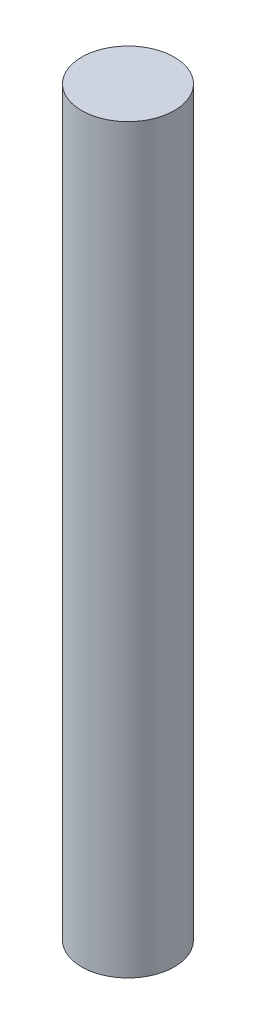
SolidWorks part; units mm, degrees
ref_plane "前视基准面" through (0, 0, 0) normal (0, 0, 1) x (1, 0, 0)
ref_plane "上视基准面" through (0, 0, 0) normal (0, 1, 0) x (1, 0, 0)
ref_plane "右视基准面" through (0, 0, 0) normal (1, 0, 0) x (0, 0, -1)
other "Configuration Table"
sketch "草图1" plane through (0, 0, 0) normal (0, 1, 0) x (1, 0, 0)
  circle A0 centre (0, 0) radius 2.5
  dimension "D1" = 5
extrude "凸台-拉伸1" add sketch "草图1" along normal blind 40
